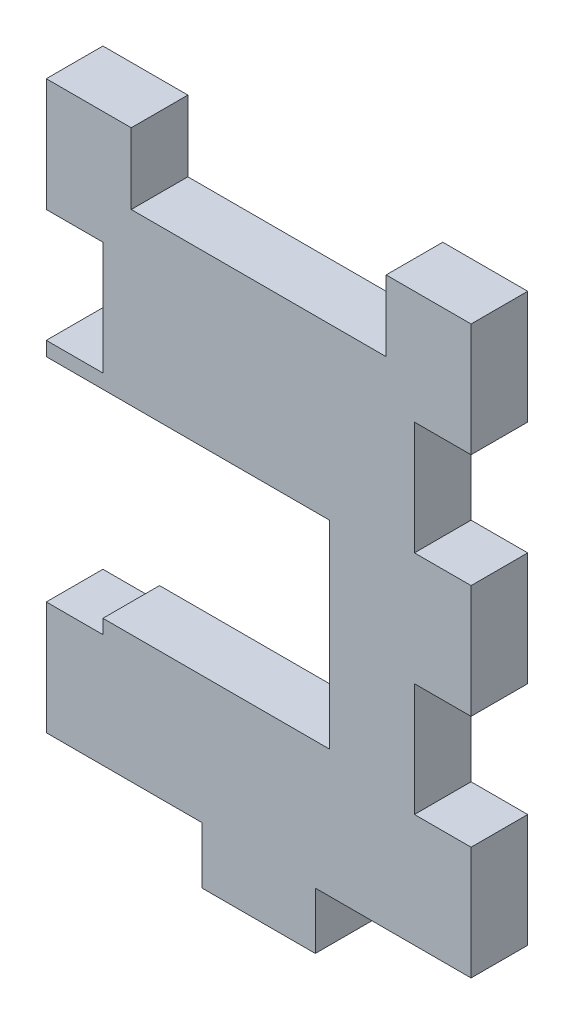
SolidWorks part; units mm, degrees
ref_plane "Front Plane" through (0, 0, 0) normal (0, 0, 1) x (1, 0, 0)
ref_plane "Top Plane" through (0, 0, 0) normal (0, 1, 0) x (1, 0, 0)
ref_plane "Right Plane" through (0, 0, 0) normal (1, 0, 0) x (0, 0, -1)
sketch "Sketch1" plane through (0, 0, 0) normal (0, 0, 1) x (1, 0, 0)
  line L1 (0, 6.35) -> (47.625, 6.35)
  line L2 (0, 6.35) -> (0, 69.85)
  line L3 (0, 69.85) -> (47.625, 69.85)
  line L4 (47.625, 6.35) -> (47.625, 69.85)
  dimension "D1" = 63.5
extrude "Boss-Extrude1" add sketch "Sketch1" along normal blind 6.35
sketch "Sketch2" plane through (0, 0, 6.35) normal (0, 0, 1) x (1, 0, 0)
  line L0 (0, 6.35) -> (47.625, 6.35) construction
  line L2 (30.1625, 0) -> (17.4625, 0)
  line L3 (30.1625, 0) -> (30.1625, 12.7)
  line L4 (30.1625, 12.7) -> (17.4625, 12.7)
  line L5 (17.4625, 0) -> (17.4625, 12.7)
  line L6 (30.1625, 0) -> (17.4625, 12.7) construction
  line L7 (30.1625, 12.7) -> (17.4625, 0) construction
  point P0 (23.8125, 6.35)
  point P3 (23.8125, 6.35)
  dimension "D1" = 12.7
  dimension "D2" = 12.7
extrude "Boss-Extrude2" add sketch "Sketch2" against normal blind 6.35
sketch "Sketch3" plane through (0, 0, 6.35) normal (0, 0, 1) x (1, 0, 0)
  line L1 (0, 19.05) -> (6.35, 19.05)
  line L2 (0, 19.05) -> (0, 31.75)
  line L3 (0, 31.75) -> (6.35, 31.75)
  line L4 (6.35, 19.05) -> (6.35, 31.75)
  line L7 (47.625, 19.05) -> (41.275, 19.05)
  line L8 (47.625, 19.05) -> (47.625, 31.75)
  line L9 (47.625, 31.75) -> (41.275, 31.75)
  line L10 (41.275, 19.05) -> (41.275, 31.75)
  line L12 (47.625, 6.35) -> (47.625, 69.85) construction
  line L13 (0, 69.85) -> (0, 6.35) construction
  line L14 (0, 6.35) -> (17.4625, 6.35) construction
  dimension "D1" = 12.7
  dimension "D2" = 6.35
  dimension "D3" = 12.7
extrude "Cut-Extrude1" cut sketch "Sketch3" against normal through all
pattern_linear "LPattern1" count 2 spacing 25.4 along (0, 1, 0) of "Cut-Extrude1"
sketch "Sketch4" plane through (0, 0, 6.35) normal (0, 0, 1) x (1, 0, 0)
  line L0 (6.35, 31.75) -> (0, 31.75) construction
  line L1 (-19.05, 20.6375) -> (31.75, 20.6375)
  line L2 (-19.05, 20.6375) -> (-19.05, 42.8625)
  line L3 (-19.05, 42.8625) -> (31.75, 42.8625)
  line L4 (31.75, 20.6375) -> (31.75, 42.8625)
  line L5 (-19.05, 20.6375) -> (31.75, 42.8625) construction
  line L6 (-19.05, 42.8625) -> (31.75, 20.6375) construction
  point P1 (6.35, 31.75)
  dimension "D1" = 50.8
  dimension "D2" = 22.225
extrude "Servo Cut" cut sketch "Sketch4" against normal through all
sketch "Sketch5" plane through (0, 0, 6.35) normal (0, 0, 1) x (1, 0, 0)
  line L0 (47.625, 69.85) -> (0, 69.85) construction
  line L1 (9.525, 61.9125) -> (38.1, 61.9125)
  line L2 (9.525, 61.9125) -> (9.525, 77.7875)
  line L3 (9.525, 77.7875) -> (38.1, 77.7875)
  line L4 (38.1, 61.9125) -> (38.1, 77.7875)
  line L5 (9.525, 61.9125) -> (38.1, 77.7875) construction
  line L6 (9.525, 77.7875) -> (38.1, 61.9125) construction
  line L7 (0, 69.85) -> (0, 57.15) construction
  point P0 (23.8125, 69.85)
  dimension "D1" = 15.875
  dimension "D2" = 9.525
extrude "Cut-Extrude2" cut sketch "Sketch5" against normal through all
